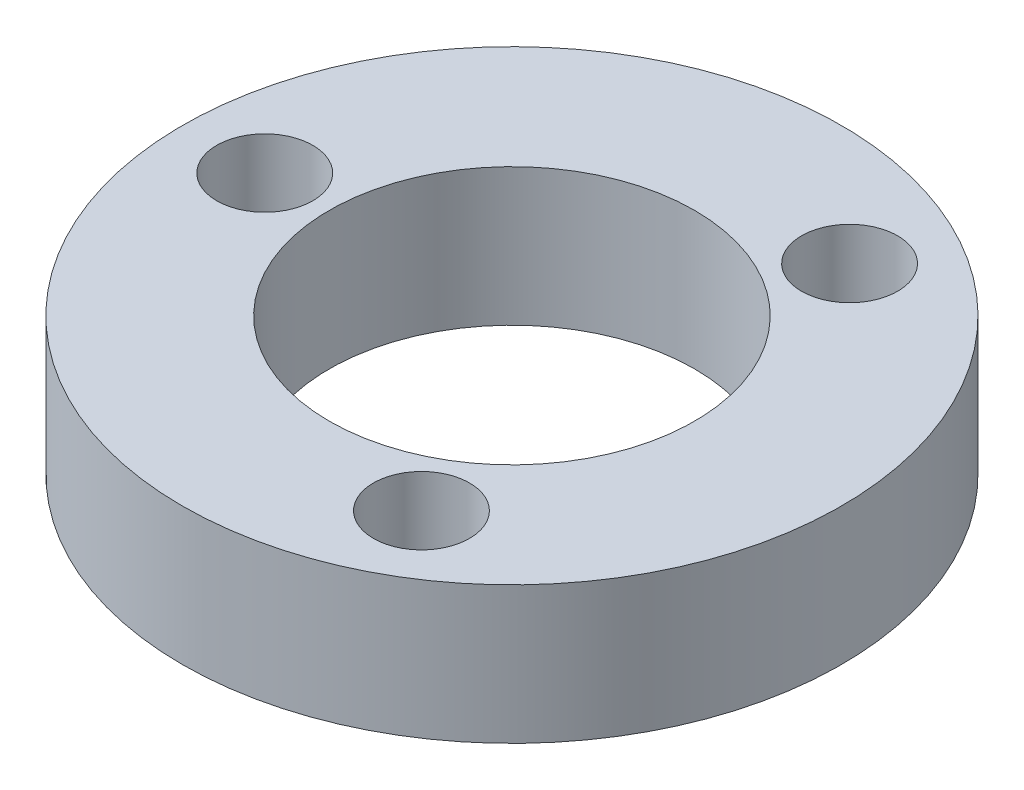
SolidWorks part; units mm, degrees
ref_plane "Спереди" through (0, 0, 0) normal (0, 0, 1) x (1, 0, 0)
ref_plane "Сверху" through (0, 0, 0) normal (0, 1, 0) x (1, 0, 0)
ref_plane "Справа" through (0, 0, 0) normal (1, 0, 0) x (0, 0, -1)
sketch "Эскиз1" plane through (0, 0, 0) normal (0, 1, 0) x (1, 0, 0)
  line L0 (0, 0) -> (-14.0959, 0) construction
  line L1 (0, 0) -> (8.6852, 15.0432) construction
  line L2 (0, 0) -> (9.7771, -16.9344) construction
  circle A0 centre (0, 0) radius 12
  circle A1 centre (0, 0) radius 6.65
  circle A2 centre (0, 0) radius 9 construction
  circle A3 centre (0, 0) radius 10.75 construction
  circle A4 centre (-9, 0) radius 1.75
  circle A5 centre (4.5, 7.7942) radius 1.75
  circle A6 centre (4.5, -7.7942) radius 1.75
  dimension "D1" = 13.3
  dimension "D2" = 24
  dimension "D3" = 18
  dimension "D4" = 21.5
  dimension "D5" = 120
  dimension "D6" = 120
extrude "Бобышка-Вытянуть1" add sketch "Эскиз1" along normal blind 5
